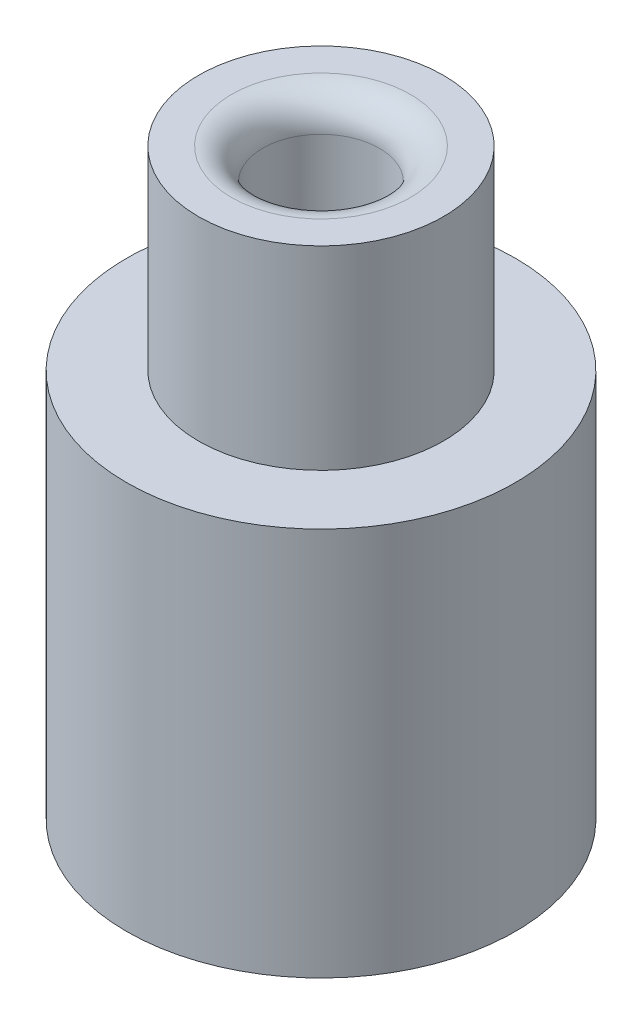
SolidWorks part; units mm, degrees
ref_plane "Front Plane" through (0, 0, 0) normal (0, 0, 1) x (1, 0, 0)
ref_plane "Top Plane" through (0, 0, 0) normal (0, 1, 0) x (1, 0, 0)
ref_plane "Right Plane" through (0, 0, 0) normal (1, 0, 0) x (0, 0, -1)
sketch "Esquisse1" plane through (0, 0, 0) normal (0, 1, 0) x (1, 0, 0)
  circle A0 centre (0, 0) radius 5
extrude "Boss.-Extru.1" add sketch "Esquisse1" along normal blind 6 and the other way blind 4
sketch "Esquisse2" plane through (0, 6, 0) normal (0, 1, 0) x (1, 0, 0)
  circle A0 centre (0, 0) radius 3.15
extrude "Boss.-Extru.2" add sketch "Esquisse2" along normal blind 5 and the other way blind 1
sketch "Esquisse3" plane through (0, 11, 0) normal (0, 1, 0) x (1, 0, 0)
  circle A0 centre (0, 0) radius 1.5
extrude "Enlèv. mat.-Extru.2" cut sketch "Esquisse3" against normal blind 10
sketch "Esquisse4" plane through (0, -4, 0) normal (0, -1, 0) x (1, 0, 0)
  circle A0 centre (0, 0) radius 2.25
extrude "Enlèv. mat.-Extru.3" cut sketch "Esquisse4" against normal blind 5
fillet "Congé1" radius 0.8 1 edges at (0, 11, 1.5)
